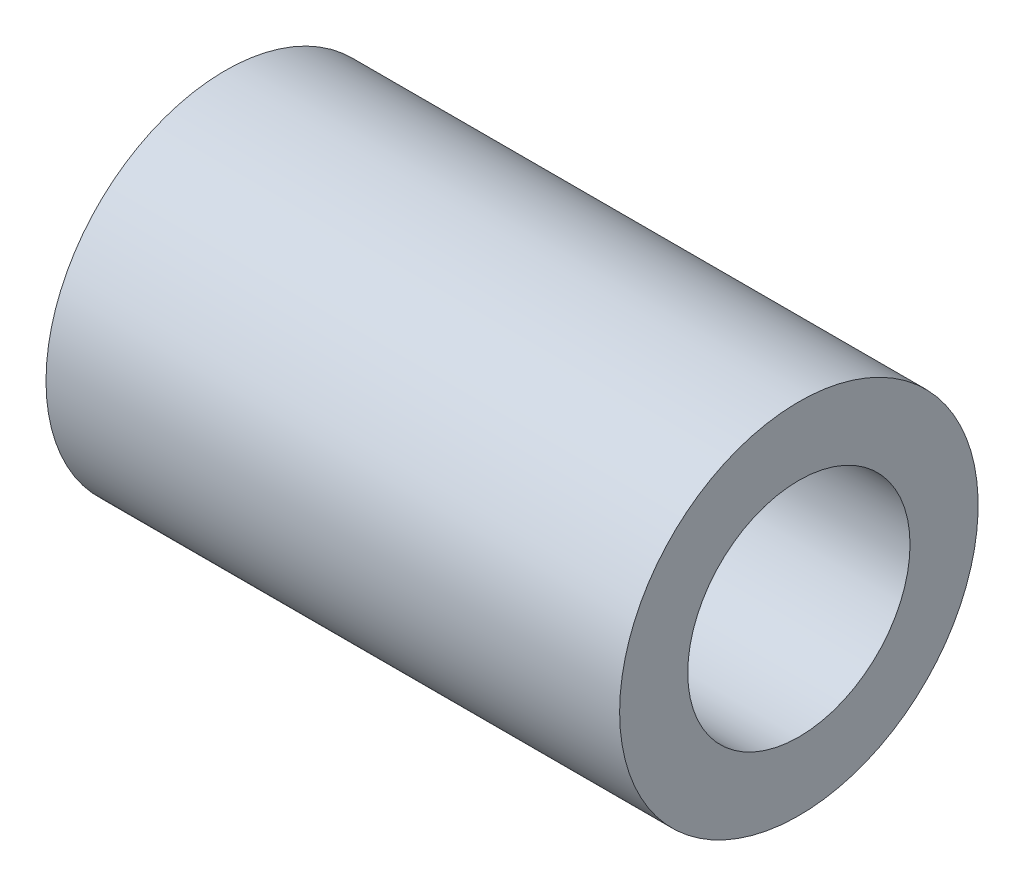
SolidWorks part; units mm, degrees
ref_plane "Front Plane" through (0, 0, 0) normal (0, 0, 1) x (1, 0, 0)
ref_plane "Top Plane" through (0, 0, 0) normal (0, 1, 0) x (1, 0, 0)
ref_plane "Right Plane" through (0, 0, 0) normal (1, 0, 0) x (0, 0, -1)
sketch "Sketch1" plane through (0, 0, 0) normal (0, 0, 1) x (1, 0, 0)
  line L0 (0, 0) -> (16, 0) construction
  line L2 (0, 3.1) -> (16, 3.1)
  line L3 (0, 3.1) -> (0, 5)
  line L4 (0, 5) -> (16, 5)
  line L5 (16, 3.1) -> (16, 5)
  dimension "W" = 16
  dimension "D_s" = 6.2
  dimension "D1_s" = 10
revolve "Revolve1" add sketch "Sketch1" angle 360 about L0
